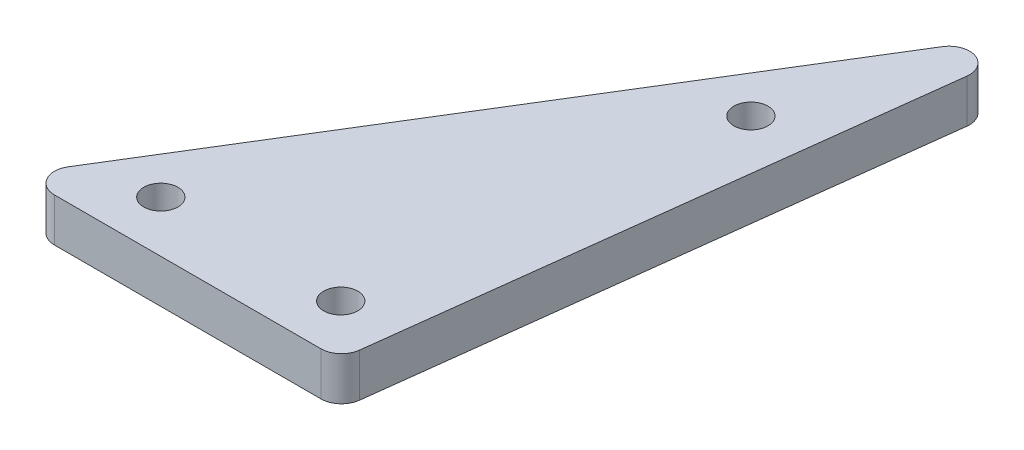
SolidWorks part; units mm, degrees
ref_plane "Front Plane" through (0, 0, 0) normal (0, 0, 1) x (1, 0, 0)
ref_plane "Top Plane" through (0, 0, 0) normal (0, 1, 0) x (1, 0, 0)
ref_plane "Right Plane" through (0, 0, 0) normal (1, 0, 0) x (0, 0, -1)
sketch "Sketch1" plane through (0, 0, 0) normal (0, 1, 0) x (1, 0, 0)
  line L0 (5.3684, 0) -> (44.3458, 0)
  line L1 (47.3235, 2.6344) -> (57.0401, 81.7704)
  line L2 (51.5075, 83.7081) -> (2.8134, 4.5722)
  arc A0 (44.3458, 0) -> (47.3235, 2.6344) centre (44.3458, 3) ccw
  arc A1 (5.3684, 0) -> (2.8134, 4.5722) centre (5.3684, 3) cw
  arc A2 (57.0401, 81.7704) -> (51.5075, 83.7081) centre (54.0625, 82.136) ccw
  point P6 (47, 0)
  point P9 (0, 0)
  point P10 (5.2237, 2.6643)
  point P11 (36.748, 54.0132)
  dimension "D3" = 3
  dimension "D1" = 97
  dimension "D2" = 47
  dimension "D7" = 24.605
extrude "Boss-Extrude1" add sketch "Sketch1" along normal blind 6.35
sketch "Sketch2" plane through (0, 6.35, 0) normal (0, 1, 0) x (1, 0, 0)
  line L0 (8.9473, 5) -> (41.9473, 5) construction
  line L1 (41.9473, 5) -> (50.1739, 72) construction
  line L2 (50.1739, 72) -> (8.9473, 5) construction
  line L6 (5.3684, 0) -> (44.3458, 0) construction
  line L7 (51.5075, 83.7081) -> (2.8134, 4.5722) construction
  circle A0 centre (13.421, 7.5) radius 2.5
  circle A1 centre (46.2955, 60.9264) radius 2.5
  circle A2 centre (39.7355, 7.5) radius 2.5
  dimension "D6" = 5
  dimension "D7" = 5
  dimension "D8" = 5
  dimension "D1" = 33
  dimension "D2" = 67
  dimension "D3" = 97
  dimension "D4" = 5
  dimension "D5" = 5
extrude "Cut-Extrude1" cut sketch "Sketch2" against normal through all
